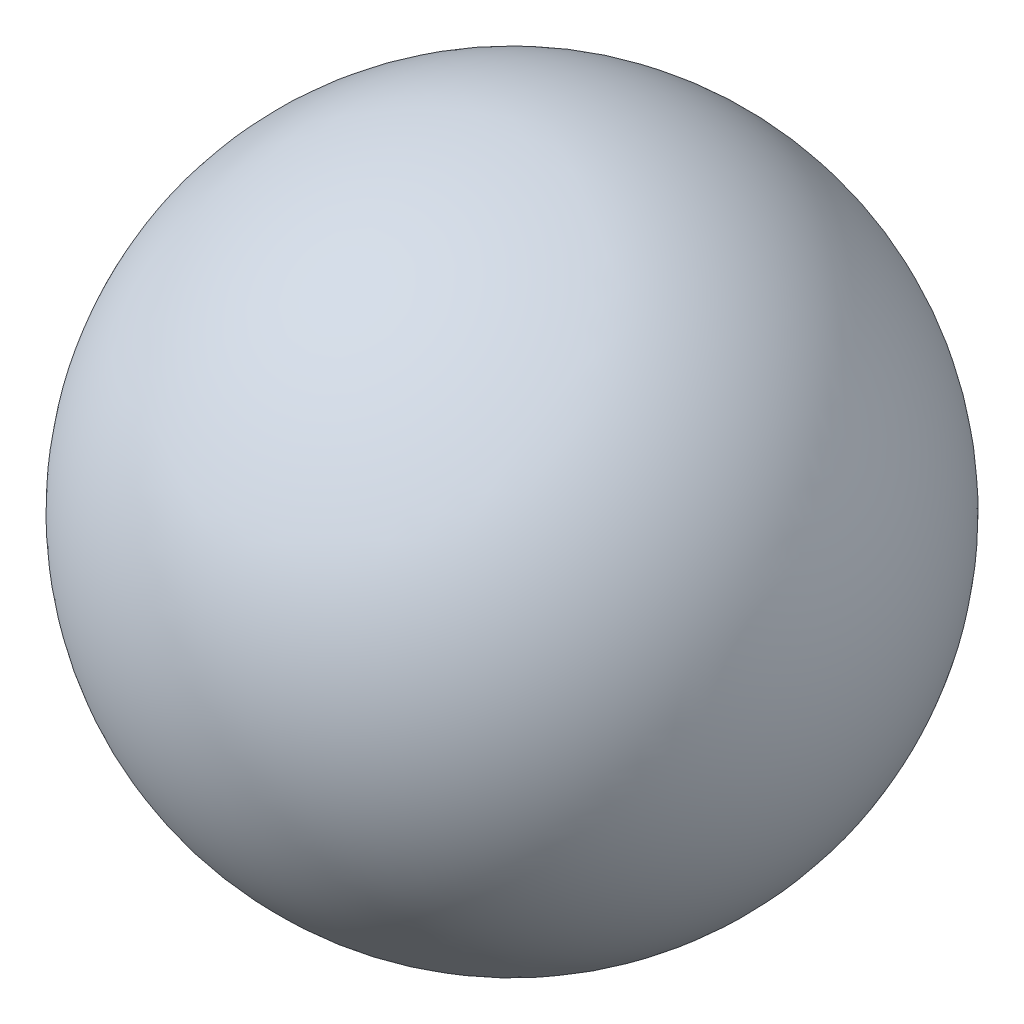
SolidWorks part; units mm, degrees
ref_plane "Plan1" through (0, 0, 0) normal (0, 0, 1) x (1, 0, 0)
ref_plane "Plan2" through (0, 0, 0) normal (0, 1, 0) x (1, 0, 0)
ref_plane "Plan3" through (0, 0, 0) normal (1, 0, 0) x (0, 0, -1)
sketch "Esquisse1" plane through (0, 0, 0) normal (0, 1, 0) x (1, 0, 0)
  line L1 (-1, 7) -> (15, 7) construction
  line L2 (-1, 14) -> (-1, 0) construction
  line L3 (15, 14) -> (15, 0) construction
  line L4 (2.2, 7) -> (11.8, 7)
  circle A1 centre (7, 7) radius 4.8 construction
  arc A2 (11.8, 7) -> (2.2, 7) centre (7, 7) ccw
revolve "Base-Révolution" add sketch "Esquisse1" angle 360 about L1
